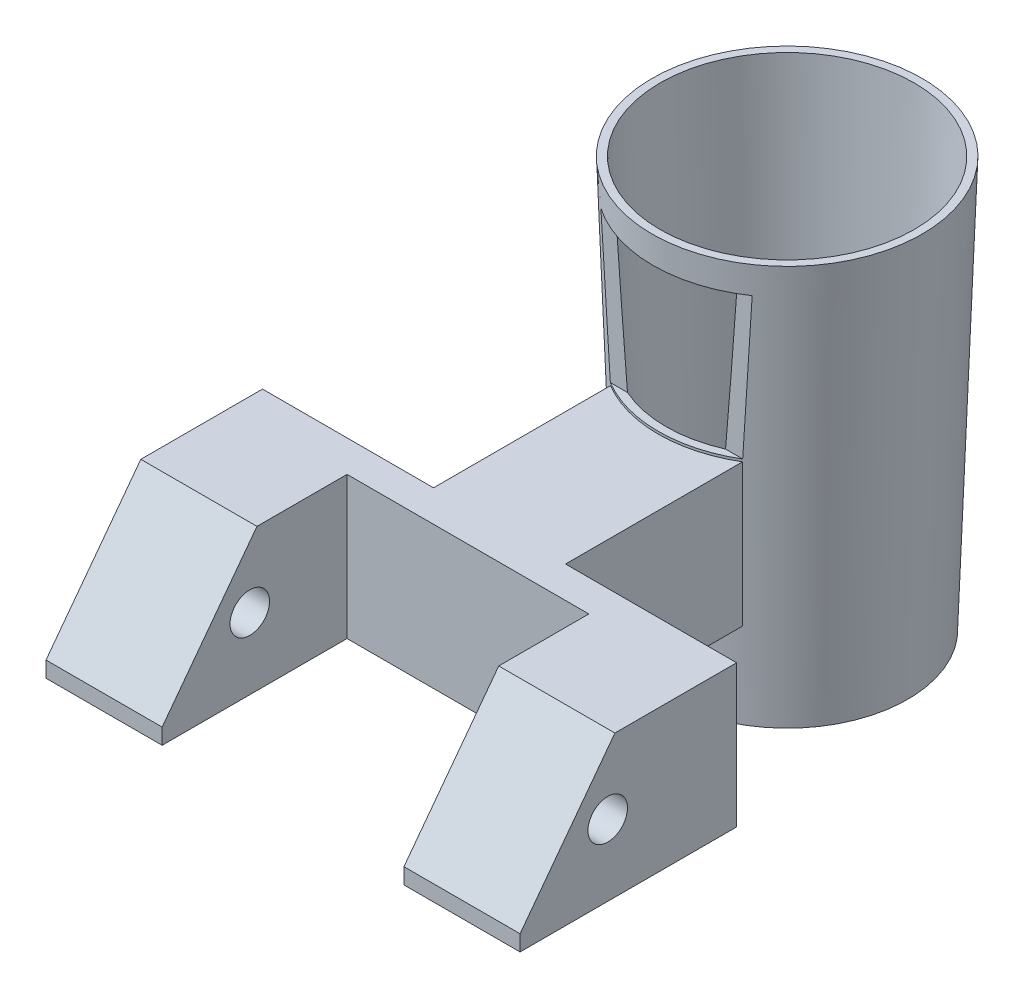
SolidWorks part; units mm, degrees
ref_plane "Front Plane" through (0, 0, 0) normal (0, 0, 1) x (1, 0, 0)
ref_plane "Top Plane" through (0, 0, 0) normal (0, 1, 0) x (1, 0, 0)
ref_plane "Right Plane" through (0, 0, 0) normal (1, 0, 0) x (0, 0, -1)
sketch "Sketch1" plane through (0, 0, 0) normal (0, 1, 0) x (1, 0, 0)
  circle A0 centre (0, 0) radius 7.635
  dimension "D1" = 15.27
extrude "Boss-Extrude1" add sketch "Sketch1" along normal blind 26.95 draft 2 draft outward yes
sketch "Sketch3" plane through (0, 26.95, 0) normal (0, 1, 0) x (1, 0, 0)
  circle A0 centre (0, 0) radius 11.552
  dimension "D1" = 23.104
ref_plane "Plane1" through (0, 0, 7) normal (0, 0, 1) x (1, 0, 0)
sketch "Sketch5" plane through (0, 0, 7) normal (0, 0, 1) x (1, 0, 0)
  line L0 (8.5761, 26.95) -> (-8.5761, 26.95) construction
  line L1 (15, 14.79) -> (-15, 14.79)
  line L2 (15, 14.79) -> (15, 5.79)
  line L3 (15, 5.79) -> (-15, 5.79)
  line L4 (-15, 14.79) -> (-15, 5.79)
  point P7 (0, 14.79)
  dimension "D1" = 12.16
  dimension "D2" = 30
  dimension "D3" = 0
  dimension "D4" = 9
extrude "Boss-Extrude3" add sketch "Sketch5" along normal blind 24.9
sketch "Sketch6" plane through (0, 0, 0) normal (0, -1, 0) x (1, 0, 0)
  circle A0 centre (0, 0) radius 7.135
  dimension "D1" = 14.27
extrude "Cut-Extrude1" cut sketch "Sketch6" against normal blind 37 draft 2 draft outward yes
sketch "Sketch7" plane through (0, 14.79, 0) normal (0, 1, 0) x (1, 0, 0)
  line L0 (-7.65, -20.2) -> (-7.65, -31.9)
  line L1 (15, -31.9) -> (-15, -31.9) construction
  line L2 (-7.65, -31.9) -> (7.65, -31.9)
  line L3 (7.65, -31.9) -> (7.65, -20.2)
  line L4 (7.65, -20.2) -> (-7.65, -20.2)
  line L5 (-15, -31.9) -> (-15, -7) construction
  line L7 (4.1769, -7) -> (4.1769, -18.2)
  line L8 (15, -31.9) -> (15, -7) construction
  line L10 (15, -18.2) -> (15, -7)
  line L11 (15, -7) -> (4.1769, -7)
  line L12 (15, -18.2) -> (4.1769, -18.2)
  line L13 (-4.1769, -7) -> (-4.1769, -18.2)
  line L14 (-4.1769, -18.2) -> (-15, -18.2)
  line L15 (-15, -18.2) -> (-15, -7)
  line L16 (-4.1769, -7) -> (-15, -7) construction
  line L17 (-15, -7) -> (-4.1769, -7)
  point P8 (0, -31.9)
  dimension "D1" = 15
  dimension "D2" = 15.3
  dimension "D3" = 11.7
  dimension "D4" = 2
  dimension "D5" = 2
extrude "Cut-Extrude2" cut sketch "Sketch7" against normal blind 38
sketch "Sketch8" plane through (-15, 0, 0) normal (-1, 0, 0) x (0, 0, 1)
  line L0 (31.9, 6.79) -> (25.9, 14.79)
  line L1 (31.9, 14.79) -> (31.9, 5.79) construction
  line L2 (31.9, 14.79) -> (18.2, 14.79) construction
  line L3 (25.9, 14.79) -> (31.9, 14.79)
  line L4 (31.9, 14.79) -> (31.9, 6.79)
  line L5 (18.2, 5.79) -> (18.2, 14.79) construction
  dimension "D1" = 1
  dimension "D2" = 7.7
extrude "Cut-Extrude3" cut sketch "Sketch8" against normal blind 32
sketch "Sketch9" plane through (-15, 0, 0) normal (-1, 0, 0) x (0, 0, 1)
  line L0 (31.9, 5.79) -> (18.2, 5.79) construction
  line L1 (31.9, 6.79) -> (31.9, 5.79) construction
  circle A0 centre (26.3537, 10.29) radius 1.25
  dimension "D1" = 2.5
  dimension "D2" = 4.5
  dimension "D3" = 5.5463
extrude "Cut-Extrude4" cut sketch "Sketch9" against normal blind 32
sketch "Sketch10" plane through (0, 0, 7) normal (0, 0, 1) x (1, 0, 0)
  line L1 (-8.75, 24.2) -> (8.75, 24.2)
  line L2 (-8.75, 24.2) -> (-8.75, 14.95)
  line L3 (-8.75, 14.95) -> (8.75, 14.95)
  line L4 (8.75, 24.2) -> (8.75, 14.95)
  line L5 (8.5761, 26.95) -> (-8.5761, 26.95) construction
  dimension "D1" = 2.75
  dimension "D2" = 9.25
  dimension "D3" = 17.5
  dimension "D4" = 8.75
extrude "Cut-Extrude5" cut sketch "Sketch10" along normal blind 15 contours L4 L3 L2 L1
extrude "Cut-Extrude6" cut sketch "Sketch3" against normal blind 1
